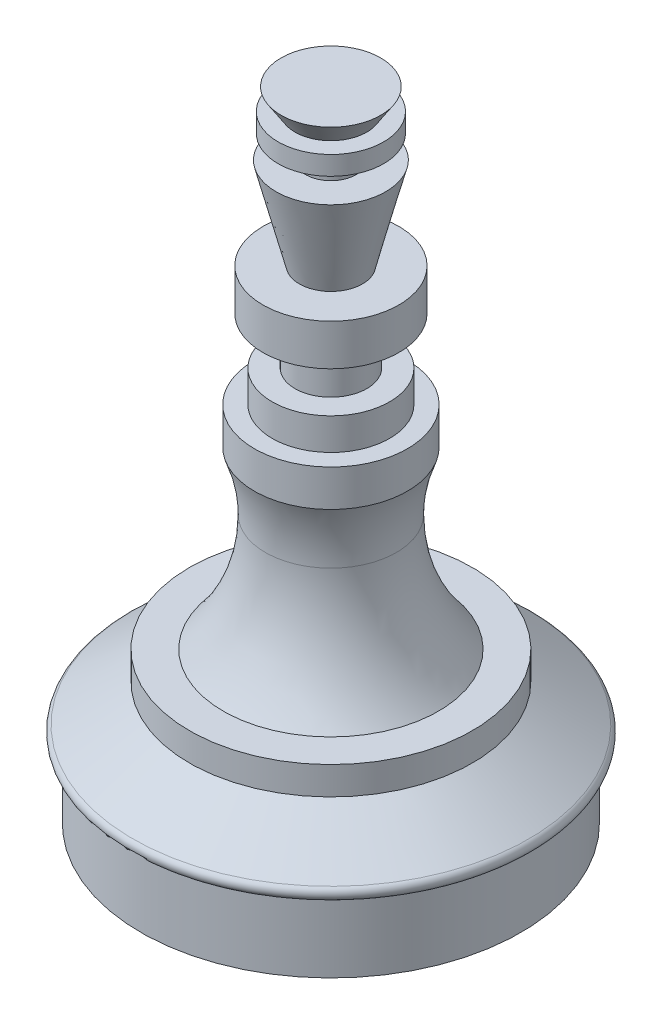
SolidWorks part; units mm, degrees
ref_plane "前基準面" through (0, 0, 0) normal (0, 0, 1) x (1, 0, 0)
ref_plane "上基準面" through (0, 0, 0) normal (0, 1, 0) x (1, 0, 0)
ref_plane "右基準面" through (0, 0, 0) normal (1, 0, 0) x (0, 0, -1)
sketch "草圖2" plane through (0, 0, 0) normal (0, 0, 1) x (1, 0, 0)
  line L0 (0, 0) -> (135.2015, 0)
  line L1 (135.2015, 0) -> (135.2015, 48.8465)
  line L2 (137.7015, 51.3465) -> (138.1178, 51.3465)
  line L3 (140.8809, 60.5137) -> (100.6818, 87.1674)
  line L4 (100.6818, 87.1674) -> (100.6818, 107.1331)
  line L5 (100.6818, 107.1331) -> (76.6055, 107.1331)
  line L6 (54.4798, 231.6769) -> (54.4798, 257.8485)
  line L7 (54.4798, 257.8485) -> (41.8035, 257.8485)
  line L8 (41.8035, 257.8485) -> (41.8035, 280.4278)
  line L9 (41.8035, 280.4278) -> (25.5574, 280.4278)
  line L10 (25.5574, 280.4278) -> (25.5574, 314.0919)
  line L11 (25.5574, 314.0919) -> (48.4121, 314.0919)
  line L12 (48.4121, 314.0919) -> (48.4121, 343.4428)
  line L13 (48.4121, 343.4428) -> (22.4952, 343.4428)
  line L14 (22.4952, 343.4428) -> (39.0073, 408.519)
  line L15 (39.0073, 408.519) -> (17.961, 408.519)
  line L16 (17.961, 408.519) -> (17.961, 425.0538)
  line L17 (17.961, 425.0538) -> (37.5578, 425.0538)
  line L18 (37.5578, 425.0538) -> (37.5578, 438.5266)
  line L19 (37.5578, 438.5266) -> (25.5574, 438.5266)
  line L20 (25.5574, 438.5266) -> (35.4144, 453.8366)
  line L21 (35.4144, 453.8366) -> (0, 453.8366)
  line L22 (0, 453.8366) -> (0, -46.4905) construction
  line L23 (0, 0) -> (0, 453.8366)
  arc A0 (76.6055, 107.1331) -> (46.6569, 189.9857) centre (176.4586, 190.0659) cw
  arc A1 (46.6569, 189.9857) -> (54.4798, 231.6769) centre (161.2849, 190.0565) cw
  arc A2 (138.1178, 51.3465) -> (140.8809, 60.5137) centre (138.1178, 56.3465) ccw
  arc A3 (135.2015, 48.8465) -> (137.7015, 51.3465) centre (137.7015, 48.8465) cw
  point P19 (135.2015, 0)
  point P30 (134.6142, 51.3465)
  point P31 (80.5893, 87.1674)
  point P32 (56.5129, 107.1331)
  point P33 (26.5643, 190.0565)
  point P34 (21.7109, 257.8485)
  point P35 (5.4648, 280.4278)
  point P36 (2.4026, 343.4428)
  point P37 (19.6372, 411.3662)
  point P38 (17.961, 408.519)
  point P39 (33.271, 425.0538)
  point P40 (0, 465.7784)
  point P41 (25.5574, 438.5266)
  point P42 (35.4144, 453.8366)
  dimension "D1" = 5
  dimension "D2" = 2.5
revolve "旋轉1" add sketch "草圖2" angle 360 about L22
scale "縮放比例1" scale about centroid uniform scaling yes scale factor 1.5
